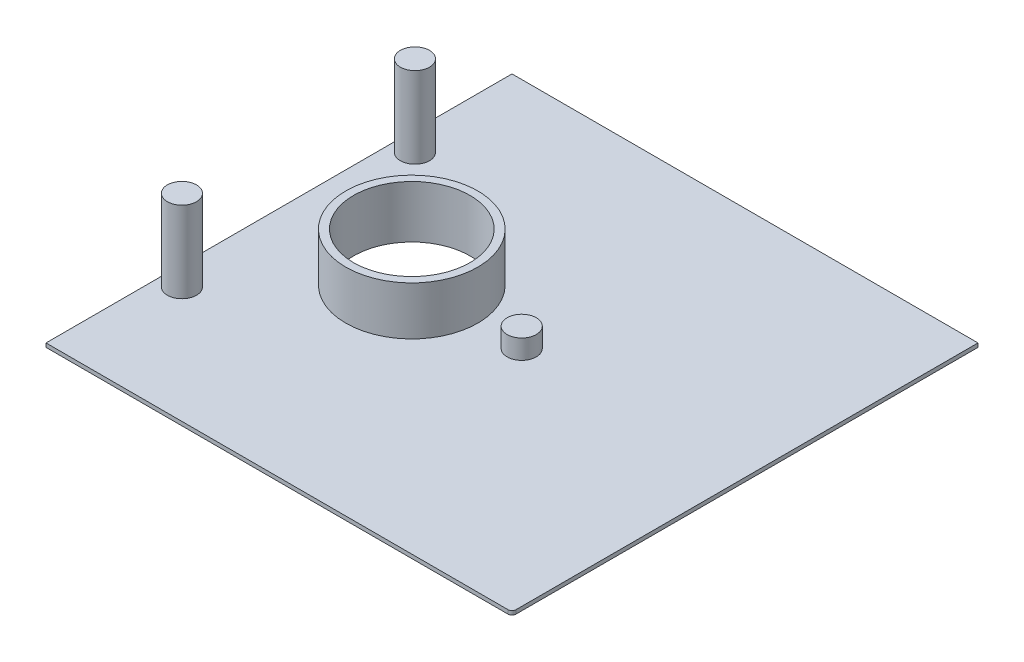
SolidWorks part; units mm, degrees
ref_plane "Front Plane" through (0, 0, 0) normal (0, 0, 1) x (1, 0, 0)
ref_plane "Top Plane" through (0, 0, 0) normal (0, 1, 0) x (1, 0, 0)
ref_plane "Right Plane" through (0, 0, 0) normal (1, 0, 0) x (0, 0, -1)
sketch "Sketch1" plane through (0, 0, 0) normal (0, 1, 0) x (1, 0, 0)
  line L1 (-101.6, 152.4) -> (203.2, 152.4)
  line L2 (-101.6, 152.4) -> (-101.6, -152.4)
  line L3 (-101.6, -152.4) -> (203.2, -152.4)
  line L4 (203.2, 152.4) -> (203.2, -152.4)
  line L5 (-101.6, 152.4) -> (203.2, -152.4) construction
  line L6 (-101.6, -152.4) -> (203.2, 152.4) construction
  point P0 (50.8, 0)
  dimension "D1" = 304.8
  dimension "D2" = 304.8
  dimension "D3" = 101.6
extrude "Boss-Extrude1" add sketch "Sketch1" along normal blind 2.54
sketch "Sketch3" plane through (0, 2.54, 0) normal (0, 1, 0) x (1, 0, 0)
  circle A0 centre (57.15, 0) radius 9.525
  dimension "D1" = 19.05
  dimension "D2" = 57.15
extrude "Boss-Extrude2" add sketch "Sketch3" along normal blind 12.7
sketch "Sketch4" plane through (0, 2.54, 0) normal (0, 1, 0) x (1, 0, 0)
  line L2 (57.15, 0) -> (-14.742, 0) construction
  circle A2 centre (-14.742, 0) radius 38.1
  dimension "D1" = 76.2
sketch "Sketch5" plane through (0, 2.54, 0) normal (0, 1, 0) x (1, 0, 0)
  circle A0 centre (-14.742, 0) radius 38.1
  dimension "D1" = 76.2
  dimension "D2" = 14.742
extrude "Cut-Extrude2" cut sketch "Sketch5" against normal through all
sketch "Sketch6" plane through (0, 0, 0) normal (0, 1, 0) x (1, 0, 0)
  circle A0 centre (57.15, 0) radius 139.7 construction
  dimension "D1" = 279.4
sketch "Sketch7" plane through (0, 2.54, 0) normal (0, 1, 0) x (1, 0, 0)
  circle A0 centre (57.15, 0) radius 139.7 construction
  circle A1 centre (-88.9, 76.2) radius 9.525
  dimension "D1" = 279.4
  dimension "D2" = 76.2
  dimension "D4" = 19.05
  dimension "D3" = 88.9
extrude "Boss-Extrude4" add sketch "Sketch7" along normal offset from surface (53.0225 mm away) 55.5625 up to face at (-14.742, 0, 38.1)
mirror "Mirror1" about plane through (0, 0, 0) normal (0, 0, 1) of "Boss-Extrude4"
fillet "Fillet1" radius 2.54 1 edges at (203.2, 1.27, 152.4)
sketch "Sketch9" plane through (0, 2.54, 0) normal (0, 1, 0) x (1, 0, 0)
  circle A0 centre (-14.742, 0) radius 43.18
  circle A1 centre (-14.742, 0) radius 38.1 construction
  circle A2 centre (-14.742, 0) radius 38.1
  dimension "D1" = 86.36
extrude "Boss-Extrude5" add sketch "Sketch9" along normal blind 31.75
